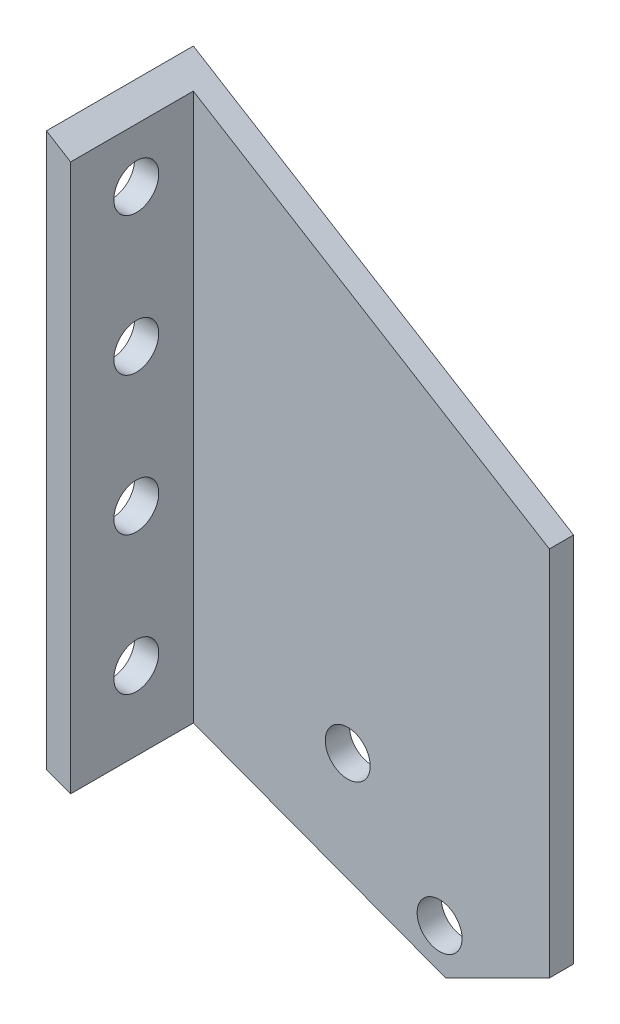
SolidWorks part; units mm, degrees
ref_plane "前视基准面" through (0, 0, 0) normal (0, 0, 1) x (1, 0, 0)
ref_plane "上视基准面" through (0, 0, 0) normal (0, 1, 0) x (1, 0, 0)
ref_plane "右视基准面" through (0, 0, 0) normal (1, 0, 0) x (0, 0, -1)
sketch "草图1" plane through (0, 0, 0) normal (0, 0, 1) x (1, 0, 0)
  line L0 (-1188.0651, 85.2964) -> (48811.9349, 85.2964) construction
  line L1 (-188.0651, -994.7583) -> (-188.0651, 49005.2417) construction
  line L2 (-1173.1343, -49.7036) -> (48826.8657, -49.7036) construction
  line L3 (-148.5651, -1041.5004) -> (-148.5651, 48958.4996) construction
  line L4 (-1169.9539, -234.7036) -> (48830.0461, -234.7036) construction
  line L5 (71.4349, -49.7036) -> (71.4349, -264.7036)
  line L6 (11.4349, -1089.7199) -> (11.4349, 48910.2801) construction
  line L7 (-972.3331, -294.7036) -> (49027.6669, -294.7036) construction
  line L8 (71.4349, -264.7036) -> (11.4349, -294.7036)
  line L9 (11.4349, -294.7036) -> (-148.5651, -234.7036)
  line L10 (-148.5651, -234.7036) -> (-148.5651, 85.2964)
  line L11 (-148.5651, 85.2964) -> (71.4349, -49.7036)
  line L12 (1811.9349, -49.7036) -> (1811.9349, -2299.7036) construction
  line L13 (1811.9349, -2299.7036) -> (-188.0651, -49.7036) construction
  circle A0 centre (-45.2269, -210.3966) radius 13
  circle A1 centre (7.9222, -270.1893) radius 13
  point P15 (11.4349, -294.7036)
  point P17 (1811.9349, -49.7036)
  point P21 (-188.0651, -49.7036)
  point P24 (-45.2269, -210.3966)
  point P26 (7.9222, -270.1893)
  dimension "D12" = 26
  dimension "D13" = 26
  dimension "D1" = 135
  dimension "D2" = 39.5
  dimension "D3" = 185
  dimension "D4" = 215
  dimension "D5" = 220
  dimension "D6" = 60
  dimension "D7" = 60
  dimension "D8" = 2000
  dimension "D9" = 2250
  dimension "D10" = 215
  dimension "D11" = 80
extrude "凸台-拉伸1" add sketch "草图1" along normal blind 14
sketch "草图2" plane through (0, 0, 14) normal (0, 0, 1) x (1, 0, 0)
  line L0 (-134.5651, 76.7055) -> (-134.5651, -239.9536)
  line L1 (71.4349, -49.7036) -> (-148.5651, 85.2964) construction
  line L2 (-148.5651, -234.7036) -> (11.4349, -294.7036) construction
  line L3 (-148.5651, 85.2964) -> (-148.5651, -234.7036) construction
  line L9 (71.4349, -49.7036) -> (-148.5651, 85.2964)
  line L10 (-148.5651, 85.2964) -> (-148.5651, -234.7036)
  line L11 (-148.5651, -234.7036) -> (11.4349, -294.7036)
  line L12 (11.4349, -294.7036) -> (71.4349, -264.7036)
  line L13 (71.4349, -264.7036) -> (71.4349, -49.7036)
  line L14 (-134.5651, 76.7055) -> (-148.5651, 85.2964)
  line L15 (-148.5651, 85.2964) -> (-148.5651, -234.7036)
  line L16 (-148.5651, -234.7036) -> (-134.5651, -239.9536)
  dimension "D1" = 14
  dimension "D2" = 0
extrude "凸台-拉伸2" add sketch "草图2" along normal blind 71
sketch "草图3" plane through (-148.5651, 0, 0) normal (-1, 0, 0) x (0, 0, 1)
  line L0 (47, -945.3498) -> (47, 49054.6502) construction
  line L1 (85, 85.2964) -> (85, -234.7036) construction
  line L2 (0, 45.2964) -> (85, 45.2964) construction
  line L3 (0, 85.2964) -> (0, -234.7036) construction
  line L4 (85, 85.2964) -> (0, 85.2964) construction
  circle A0 centre (47, 45.2964) radius 13
  dimension "D3" = 26
  dimension "D1" = 38
  dimension "D2" = 40
extrude "切除-拉伸1" cut sketch "草图3" against normal through all
pattern_linear "阵列(线性)1" count 4 spacing 80 along (0, -1, 0) of "切除-拉伸1"
